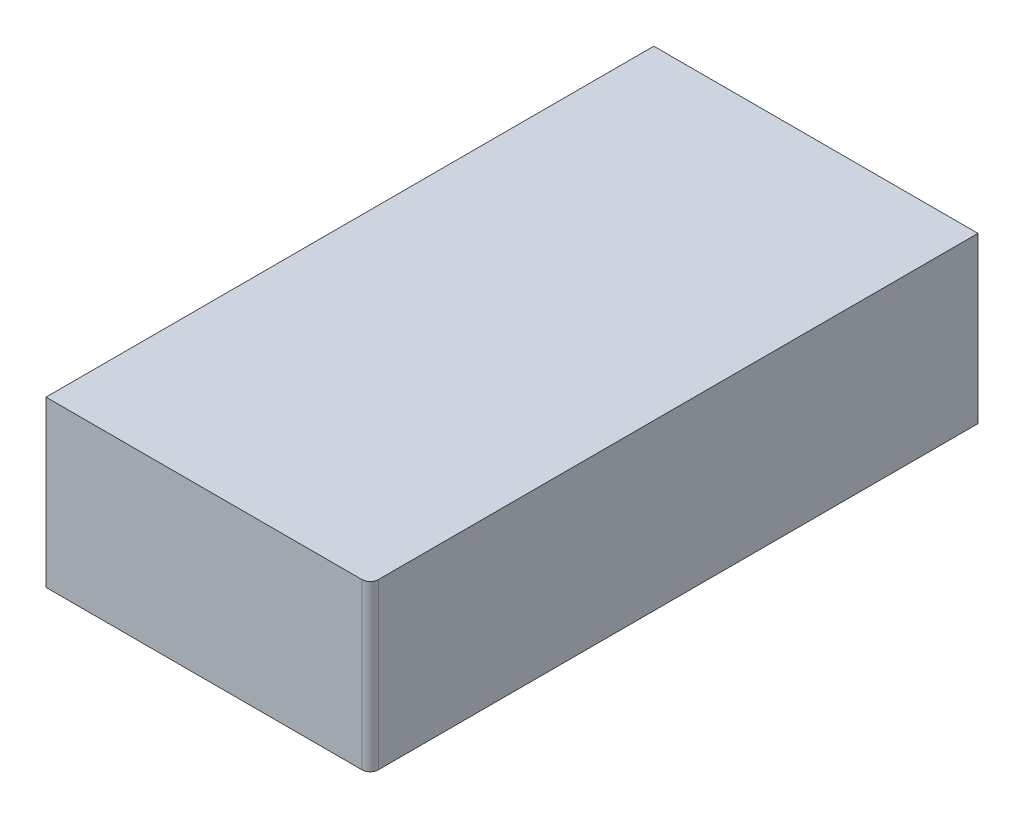
SolidWorks part; units mm, degrees
ref_plane "前视基准面" through (0, 0, 0) normal (0, 0, 1) x (1, 0, 0)
ref_plane "上视基准面" through (0, 0, 0) normal (0, 1, 0) x (1, 0, 0)
ref_plane "右视基准面" through (0, 0, 0) normal (1, 0, 0) x (0, 0, -1)
sketch "草图1" plane through (0, 0, 0) normal (0, 0, 1) x (1, 0, 0)
  line L1 (425, 0) -> (305, 0)
  line L2 (425, 0) -> (425, -61)
  line L3 (425, -61) -> (305, -61)
  line L4 (305, 0) -> (305, -61)
  dimension "D1" = 61
  dimension "D2" = 120
extrude "凸台-拉伸1" add sketch "草图1" against normal offset from surface (225 mm away) 90
fillet "圆角1" radius 3 1 edges at (425, -30.5, 0)
